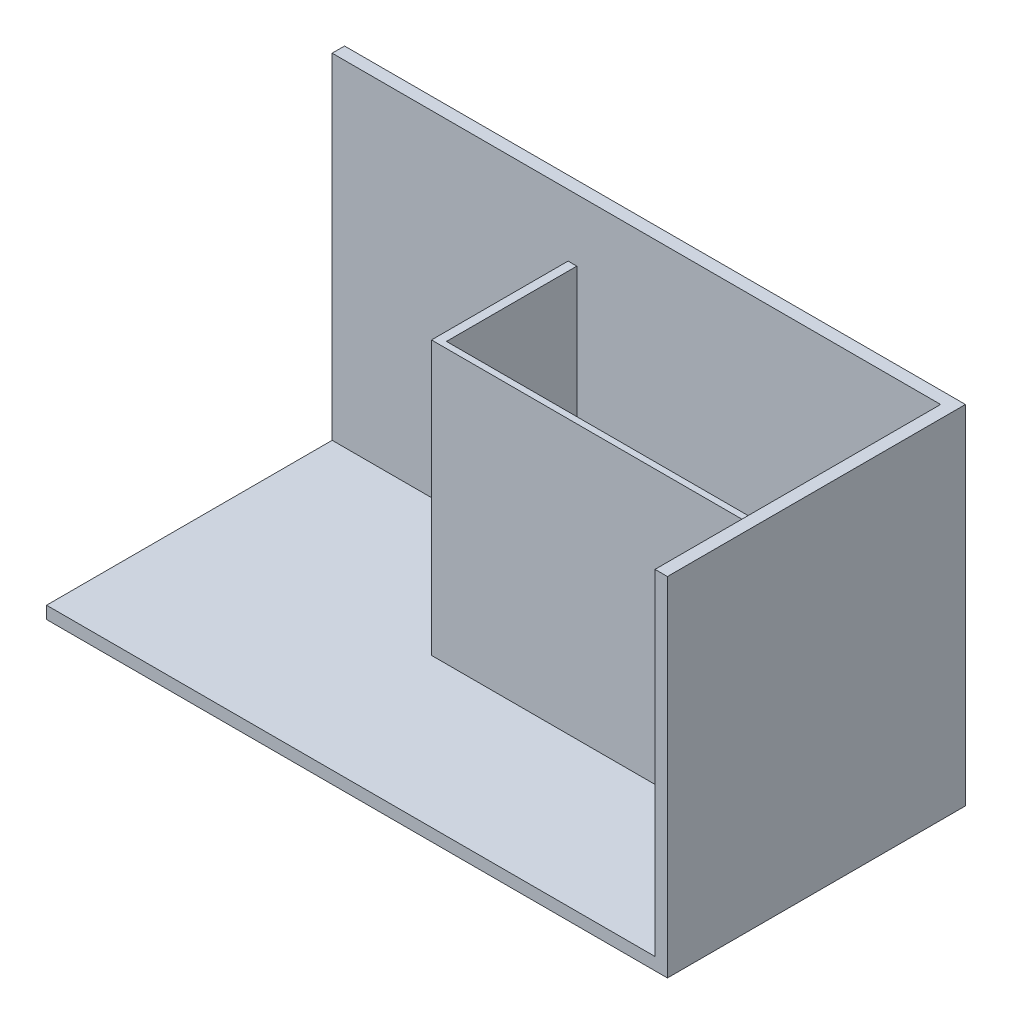
SolidWorks part; units mm, degrees
ref_plane "Plan de face" through (0, 0, 0) normal (0, 0, 1) x (1, 0, 0)
ref_plane "Plan de dessus" through (0, 0, 0) normal (0, 1, 0) x (1, 0, 0)
ref_plane "Plan de droite" through (0, 0, 0) normal (1, 0, 0) x (0, 0, -1)
sketch "Esquisse1" plane through (0, 0, 0) normal (0, 1, 0) x (1, 0, 0)
  line L1 (-66.3541, 2344.4284) -> (4933.6459, 2344.4284)
  line L2 (-66.3541, 2344.4284) -> (-66.3541, -55.5716)
  line L3 (-66.3541, -55.5716) -> (4933.6459, -55.5716)
  line L4 (4933.6459, 2344.4284) -> (4933.6459, -55.5716)
extrude "Boss.-Extru.1" add sketch "Esquisse1" against normal blind 100
sketch "Esquisse2" plane through (0, 0, -2344.4284) normal (0, 0, -1) x (-1, 0, 0)
  line L2 (-4933.6459, 0) -> (66.3541, 0)
  line L3 (-4933.6459, 0) -> (-4933.6459, 2700)
  line L4 (-4933.6459, 2700) -> (66.3541, 2700)
  line L7 (66.3541, 0) -> (66.3541, 2700)
  dimension "D1" = 5000
  dimension "D2" = 2700
extrude "Boss.-Extru.2" add sketch "Esquisse2" against normal blind 100
sketch "Esquisse3" plane through (4933.6459, 0, 0) normal (1, 0, 0) x (0, 0, -1)
  line L0 (2344.4284, -100) -> (2344.4284, 2700) construction
  line L1 (2344.4284, 0) -> (-55.5716, 0)
  line L2 (2344.4284, 0) -> (2344.4284, 2700)
  line L3 (2344.4284, 2700) -> (-55.5716, 2700)
  line L4 (-55.5716, 0) -> (-55.5716, 2700)
extrude "Boss.-Extru.3" add sketch "Esquisse3" against normal blind 100
sketch "Esquisse22" plane through (0, 0, 0) normal (0, 1, 0) x (1, 0, 0)
  line L0 (4833.6459, 2244.4284) -> (4833.6459, 1144.4284) construction
  line L1 (4833.6459, -55.5716) -> (4833.6459, 2244.4284) construction
  line L2 (4833.6459, 1144.4284) -> (1833.6459, 1144.4284) construction
  line L3 (1833.6459, 1144.4284) -> (1833.6459, 2244.4284) construction
  line L4 (4833.6459, 2244.4284) -> (-66.3541, 2244.4284) construction
  line L6 (1833.6459, 2244.4284) -> (1904.0489, 2244.4284)
  line L7 (1833.6459, 2244.4284) -> (1833.6459, 1144.4284)
  line L8 (1833.6459, 1144.4284) -> (1904.0489, 1144.4284)
  line L9 (1904.0489, 2244.4284) -> (1904.0489, 1144.4284)
extrude "Boss.-Extru.8" add sketch "Esquisse22" along normal blind 2200
sketch "Esquisse23" plane through (0, 0, 0) normal (0, 1, 0) x (1, 0, 0)
  line L0 (1833.6459, 1144.4284) -> (4833.6459, 1144.4284) construction
  line L2 (4833.6459, -55.5716) -> (4833.6459, 2244.4284) construction
  line L4 (1833.6459, 1144.4284) -> (4833.6459, 1144.4284)
  line L5 (1833.6459, 1144.4284) -> (1833.6459, 1194.4284)
  line L6 (1833.6459, 1194.4284) -> (4833.6459, 1194.4284)
  line L7 (4833.6459, 1144.4284) -> (4833.6459, 1194.4284)
extrude "Boss.-Extru.9" add sketch "Esquisse23" along normal blind 2200
